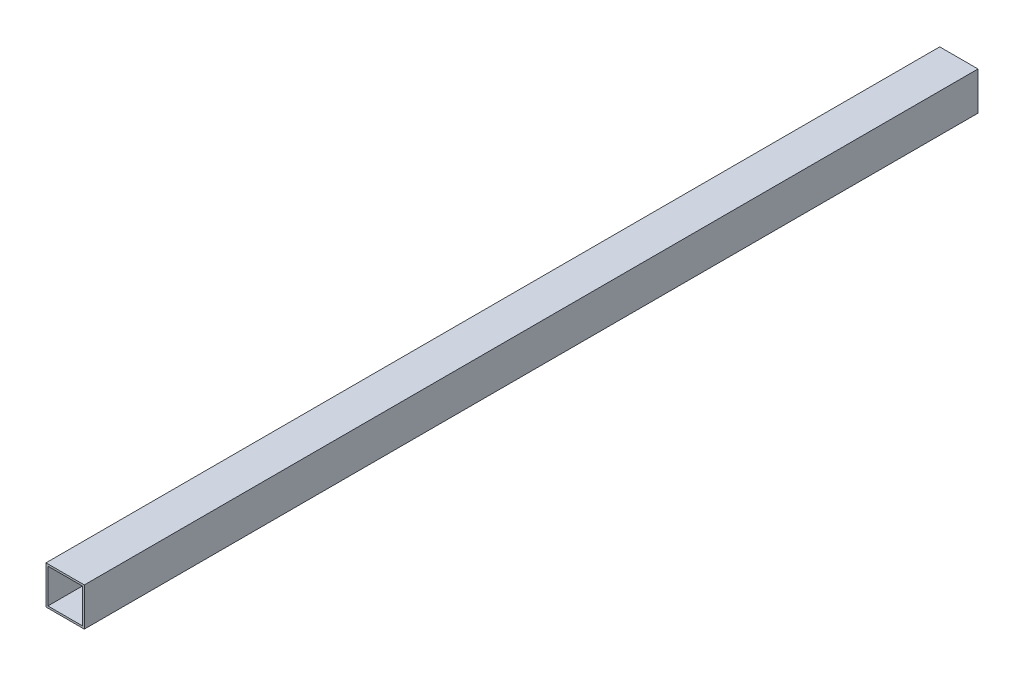
SolidWorks part; units mm, degrees
material "1060 Alloy"
ref_plane "Front Plane" through (0, 0, 0) normal (0, 0, 1) x (1, 0, 0)
ref_plane "Top Plane" through (0, 0, 0) normal (0, 1, 0) x (1, 0, 0)
ref_plane "Right Plane" through (0, 0, 0) normal (1, 0, 0) x (0, 0, -1)
sketch "Sketch1" plane through (0, 0, 0) normal (0, 0, 1) x (1, 0, 0)
  line L0 (-27, 27) -> (27, 27)
  line L1 (-30, -30) -> (30, -30)
  line L2 (-30, -30) -> (-30, 30)
  line L3 (-30, 30) -> (30, 30)
  line L4 (30, -30) -> (30, 30)
  line L5 (-30, -30) -> (30, 30) construction
  line L6 (-30, 30) -> (30, -30) construction
  line L7 (27, -27) -> (27, 27)
  line L8 (-27, -27) -> (27, -27)
  line L9 (-27, -27) -> (-27, 27)
  point P0 (0, 0)
  dimension "D1" = 60
  dimension "D2" = 60
  dimension "D3" = 3
extrude "Boss-Extrude1" add sketch "Sketch1" along normal blind 1400
